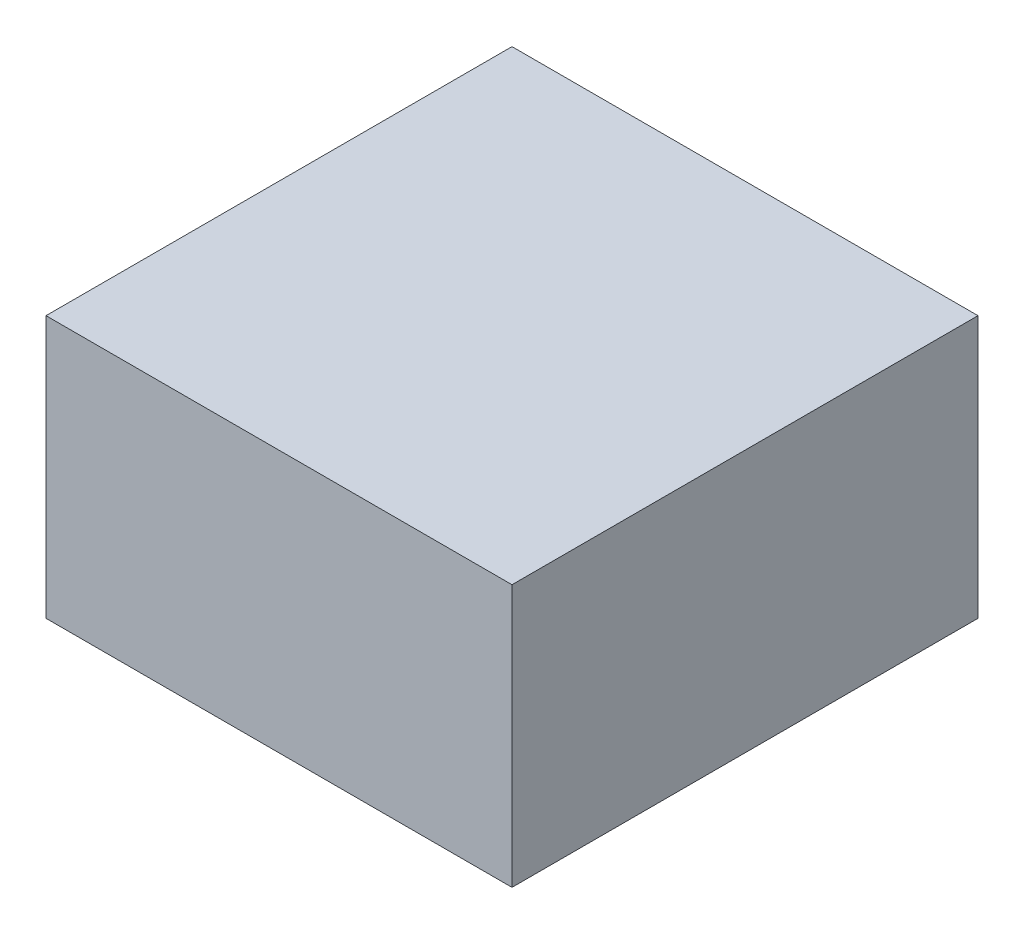
SolidWorks part; units mm, degrees
ref_plane "Front Plane" through (0, 0, 0) normal (0, 0, 1) x (1, 0, 0)
ref_plane "Top Plane" through (0, 0, 0) normal (0, 1, 0) x (1, 0, 0)
ref_plane "Right Plane" through (0, 0, 0) normal (1, 0, 0) x (0, 0, -1)
sketch "Sketch1" plane through (0, 0, 0) normal (0, 1, 0) x (1, 0, 0)
  line L1 (-25.4, 25.4) -> (25.4, 25.4)
  line L2 (-25.4, 25.4) -> (-25.4, -25.4)
  line L3 (-25.4, -25.4) -> (25.4, -25.4)
  line L4 (25.4, 25.4) -> (25.4, -25.4)
  line L5 (-25.4, 25.4) -> (25.4, -25.4) construction
  line L6 (-25.4, -25.4) -> (25.4, 25.4) construction
  point P0 (0, 0)
  dimension "D1" = 50.8
extrude "Boss-Extrude1" add sketch "Sketch1" along normal blind 28.575
